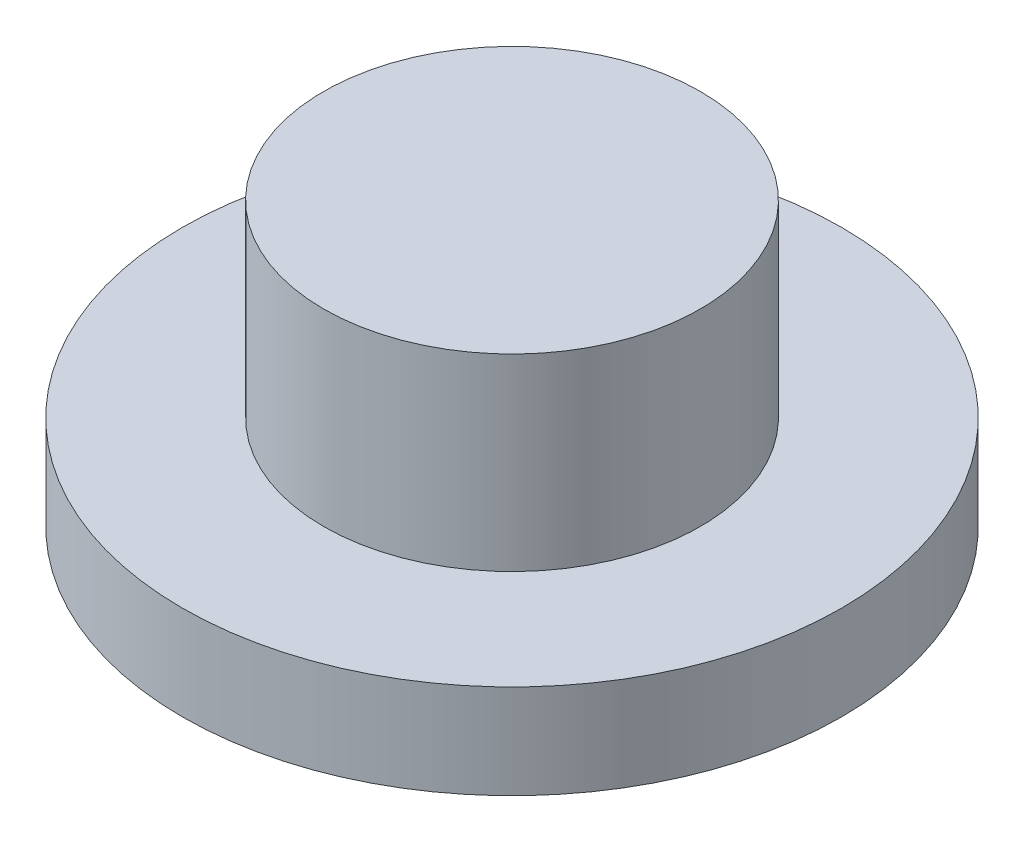
SolidWorks part; units mm, degrees
ref_plane "Front Plane" through (0, 0, 0) normal (0, 0, 1) x (1, 0, 0)
ref_plane "Top Plane" through (0, 0, 0) normal (0, 1, 0) x (1, 0, 0)
ref_plane "Right Plane" through (0, 0, 0) normal (1, 0, 0) x (0, 0, -1)
sketch "Sketch1" plane through (0, 0, 0) normal (0, 1, 0) x (1, 0, 0)
  circle A0 centre (0, 0) radius 35
  dimension "D1" = 70
extrude "Boss-Extrude1" add sketch "Sketch1" along normal blind 10
sketch "Sketch2" plane through (0, 10, 0) normal (0, 1, 0) x (1, 0, 0)
  circle A0 centre (0, 0) radius 20
  dimension "D1" = 40
extrude "Boss-Extrude2" add sketch "Sketch2" along normal blind 20
